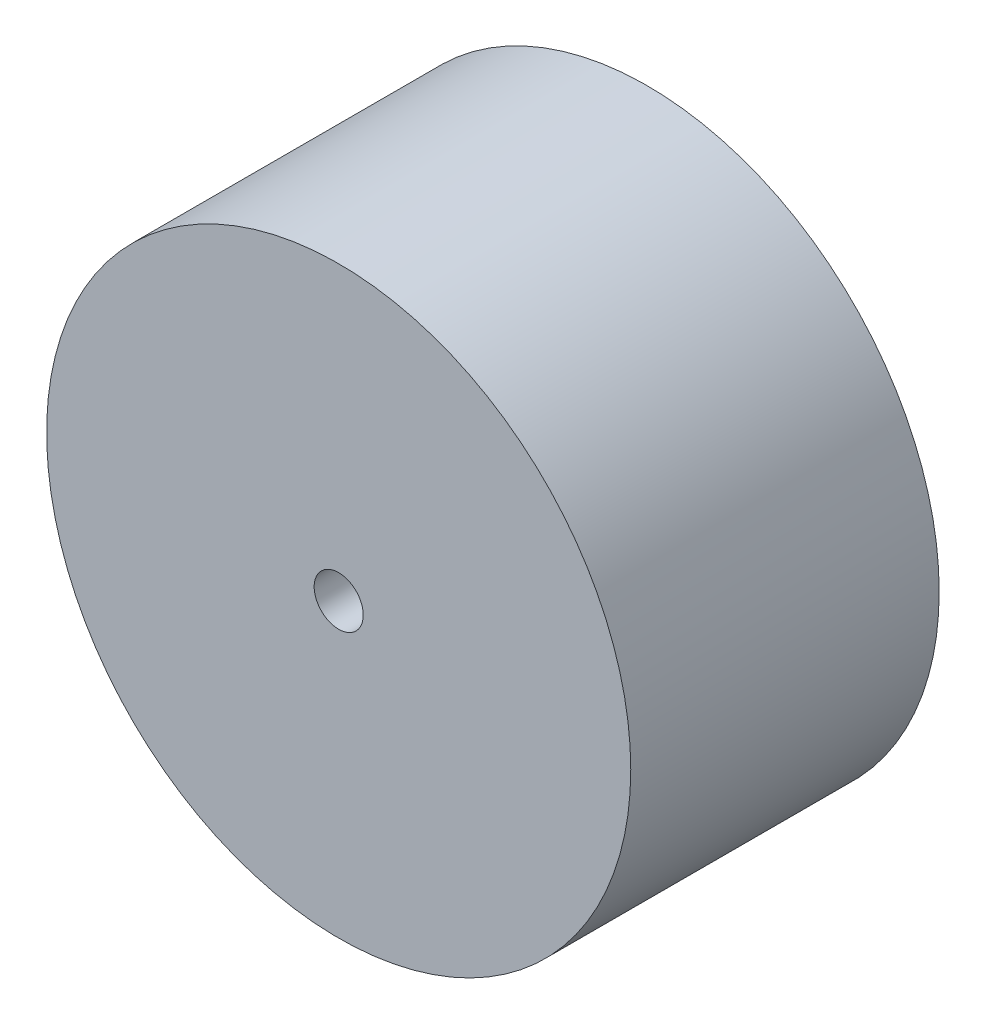
SolidWorks part; units mm, degrees
ref_plane "Front Plane" through (0, 0, 0) normal (0, 0, 1) x (1, 0, 0)
ref_plane "Top Plane" through (0, 0, 0) normal (0, 1, 0) x (1, 0, 0)
ref_plane "Right Plane" through (0, 0, 0) normal (1, 0, 0) x (0, 0, -1)
sketch "Sketch1" plane through (0, 0, 0) normal (0, 0, 1) x (1, 0, 0)
  circle A0 centre (0, 0) radius 25
  dimension "D1" = 50
extrude "Boss-Extrude1" add sketch "Sketch1" along normal mid plane 26.4
hole_wizard "Tap Drill for M5x0.8 Tap1" positions "Sketch2" profile "Sketch3" hole size "M5x0.8" standard "ANSI Metric"
sketch "Sketch2" plane through (0, 0, 13.2) normal (0, 0, 1) x (1, 0, 0)
  point P0 (0, 0)
sketch "Sketch3" plane through (0, 0, 13.2) normal (1, 0, 0) x (0, -1, 0)
  line L0 (0, 0) -> (0, 7.6118)
  line L1 (0, 7.6118) -> (2.1, 6.35)
  line L2 (2.1, 6.35) -> (2.1, 0)
  line L5 (2.1, 0) -> (0, 0)
  line L10 (0, 7.6118) -> (-2.1, 6.35) construction
  line L11 (0, -6.35) -> (0, 107.95) construction
  dimension "Hole Dia." = 4.2
  dimension "Hole Depth" = 6.35
  dimension "Drill Angle" = 118
